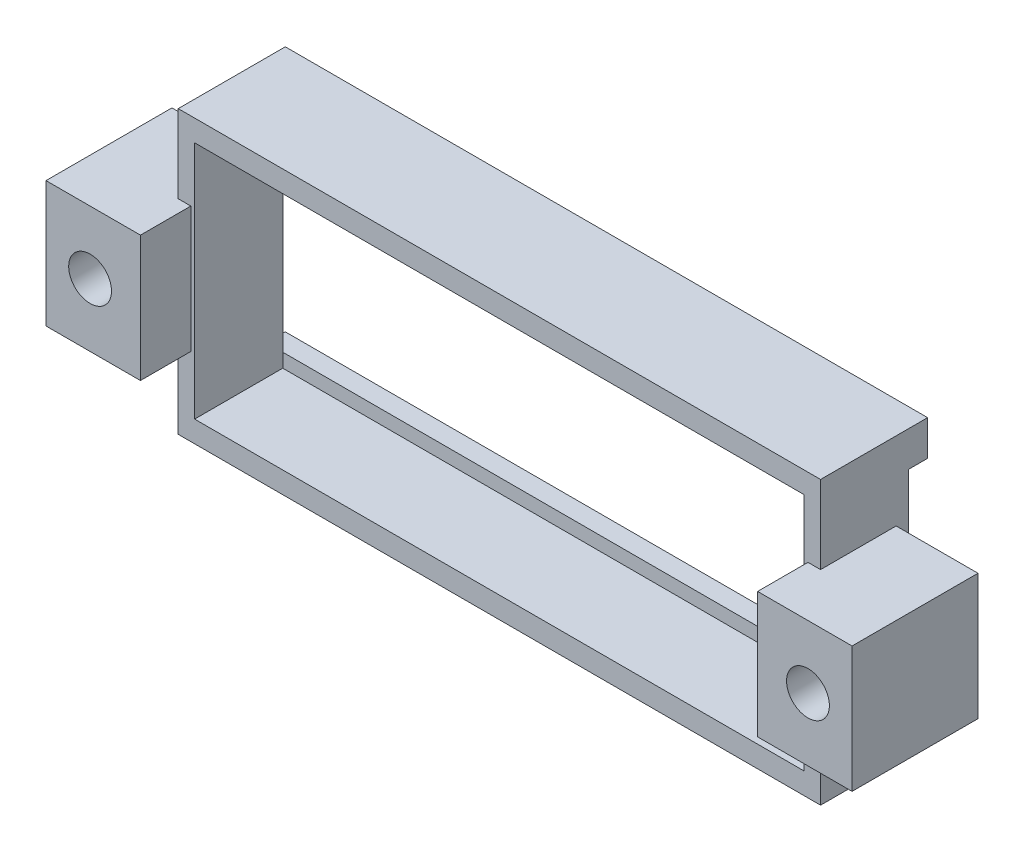
SolidWorks part; units mm, degrees
ref_plane "前视基准面" through (0, 0, 0) normal (0, 0, 1) x (1, 0, 0)
ref_plane "上视基准面" through (0, 0, 0) normal (0, 1, 0) x (1, 0, 0)
ref_plane "右视基准面" through (0, 0, 0) normal (1, 0, 0) x (0, 0, -1)
other "Configuration Table"
sketch "草图1" plane through (0, 0, 0) normal (0, 0, 1) x (1, 0, 0)
  line L1 (-25.5, -11.2) -> (25.5, -11.2)
  line L2 (-25.5, -11.2) -> (-25.5, 11.2)
  line L3 (-25.5, 11.2) -> (25.5, 11.2)
  line L4 (25.5, -11.2) -> (25.5, 11.2)
  line L6 (-24.2, -9.5) -> (24.2, -9.5)
  line L7 (-24.2, -9.5) -> (-24.2, 9.5)
  line L8 (-24.2, 9.5) -> (24.2, 9.5)
  line L9 (24.2, -9.5) -> (24.2, 9.5)
extrude "Gray_housing_perimeter_retention" add sketch "草图1" along normal blind 7 from offset 11
sketch "草图2" plane through (0, 0, 0) normal (0, 0, 1) x (1, 0, 0)
  line L1 (-25.5, -11.2) -> (25.5, -11.2)
  line L2 (-25.5, -11.2) -> (-25.5, -8.4)
  line L3 (-25.5, -8.4) -> (25.5, -8.4)
  line L4 (25.5, -11.2) -> (25.5, -8.4)
  line L6 (-25.5, 8.4) -> (25.5, 8.4)
  line L7 (-25.5, 8.4) -> (-25.5, 11.2)
  line L8 (-25.5, 11.2) -> (25.5, 11.2)
  line L9 (25.5, 8.4) -> (25.5, 11.2)
extrude "Gray_lower_edge_retaining_lips" add sketch "草图2" along normal blind 1.5 from offset 9.5
sketch "草图3" plane through (0, 0, 0) normal (0, 0, 1) x (1, 0, 0)
  line L1 (-32, -5) -> (-24.5, -5)
  line L2 (-32, -5) -> (-32, 5)
  line L3 (-32, 5) -> (-24.5, 5)
  line L4 (-24.5, -5) -> (-24.5, 5)
  line L6 (24.5, -5) -> (32, -5)
  line L7 (24.5, -5) -> (24.5, 5)
  line L8 (24.5, 5) -> (32, 5)
  line L9 (32, -5) -> (32, 5)
sketch "草图4" plane through (0, 0, 0) normal (0, 0, 1) x (1, 0, 0)
  circle A0 centre (-28.5, 0) radius 1.7
  circle A1 centre (28.5, 0) radius 1.7
sketch "草图5" plane through (0, 0, 0) normal (0, 0, 1) x (1, 0, 0)
  line L1 (-32, -5) -> (-24.5, -5)
  line L2 (-32, -5) -> (-32, 5)
  line L3 (-32, 5) -> (-24.5, 5)
  line L4 (-24.5, -5) -> (-24.5, 5)
  line L6 (24.5, -5) -> (32, -5)
  line L7 (24.5, -5) -> (24.5, 5)
  line L8 (24.5, 5) -> (32, 5)
  line L9 (32, -5) -> (32, 5)
extrude "Gray_mounting_ends_to_deck" add sketch "草图5" along normal blind 10 from offset 12
sketch "草图6" plane through (0, 0, 0) normal (0, 0, 1) x (1, 0, 0)
  circle A0 centre (-28.5, 0) radius 1.7
  circle A1 centre (28.5, 0) radius 1.7
extrude "Gray_M3_mounts" cut sketch "草图6" against normal blind 12 from offset 23
